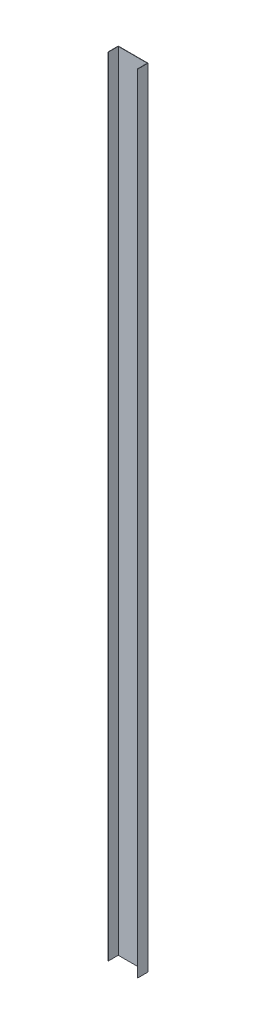
SolidWorks part; units mm, degrees
ref_plane "Front Plane" through (0, 0, 0) normal (0, 0, 1) x (1, 0, 0)
ref_plane "Top Plane" through (0, 0, 0) normal (0, 1, 0) x (1, 0, 0)
ref_plane "Right Plane" through (0, 0, 0) normal (1, 0, 0) x (0, 0, -1)
sketch "Sketch1" plane through (0, 0, 0) normal (0, 1, 0) x (1, 0, 0)
  line L1 (-46.0375, 15.875) -> (46.0375, 15.875)
  line L2 (-46.0375, 15.875) -> (-46.0375, -15.875)
  line L3 (-46.0375, -15.875) -> (46.0375, -15.875)
  line L4 (46.0375, 15.875) -> (46.0375, -15.875)
  line L5 (-46.0375, 15.875) -> (46.0375, -15.875) construction
  line L6 (-46.0375, -15.875) -> (46.0375, 15.875) construction
  point P0 (0, 0)
  dimension "D1" = 92.075
  dimension "D2" = 31.75
extrude "Boss-Extrude1" add sketch "Sketch1" along normal blind 2438.4
sketch "Sketch2" plane through (0, 0, 0) normal (0, 1, 0) x (1, 0, 0)
  line L1 (-45.0375, -16.875) -> (45.0375, -16.875)
  line L2 (-45.0375, -16.875) -> (-45.0375, 14.875)
  line L3 (-45.0375, 14.875) -> (45.0375, 14.875)
  line L4 (45.0375, -16.875) -> (45.0375, 14.875)
  line L5 (-45.0375, -16.875) -> (45.0375, 14.875) construction
  line L6 (-45.0375, 14.875) -> (45.0375, -16.875) construction
  line L7 (0, 0) -> (0, -1) construction
  line L8 (-46.0375, 15.875) -> (-46.0375, -15.875) construction
  line L9 (46.0375, 15.875) -> (-46.0375, 15.875) construction
  point P0 (0, -1)
  point P5 (43.9218, -6.6406)
  point P10 (0.794, -26.2671)
  point P11 (0, -3.3082)
  point P12 (-46.8375, -6.0587)
  dimension "D1" = 1
  dimension "D2" = 1
  dimension "D3" = 1
extrude "Cut-Extrude1" cut sketch "Sketch2" along normal blind 2438.4
